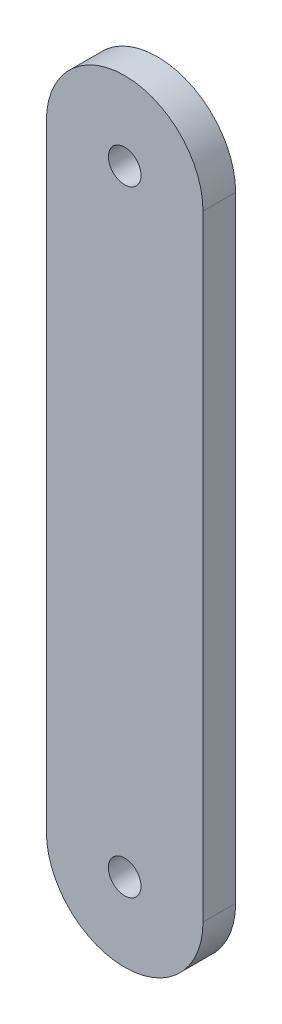
SolidWorks part; units mm, degrees
ref_plane "前视基准面" through (0, 0, 0) normal (0, 0, 1) x (1, 0, 0)
ref_plane "上视基准面" through (0, 0, 0) normal (0, 1, 0) x (1, 0, 0)
ref_plane "右视基准面" through (0, 0, 0) normal (1, 0, 0) x (0, 0, -1)
ref_plane "基准面4" through (0, 0, 5) normal (0, 0, 1) x (1, 0, 0)
sketch "草图1" plane through (0, 0, 5) normal (0, 0, 1) x (1, 0, 0)
  line L0 (12, -47.16) -> (12, 47.16)
  line L1 (-12, 47.16) -> (-12, -47.16)
  circle A0 centre (0, -47.16) radius 2.5
  circle A1 centre (0, 47.16) radius 2.5
  arc A2 (12, 47.16) -> (-12, 47.16) centre (0, 47.16) ccw
  arc A3 (-12, -47.16) -> (12, -47.16) centre (0, -47.16) ccw
  dimension "D1" = 5
  dimension "D2" = 5
extrude "凸台-拉伸1" add sketch "草图1" against normal blind 5
